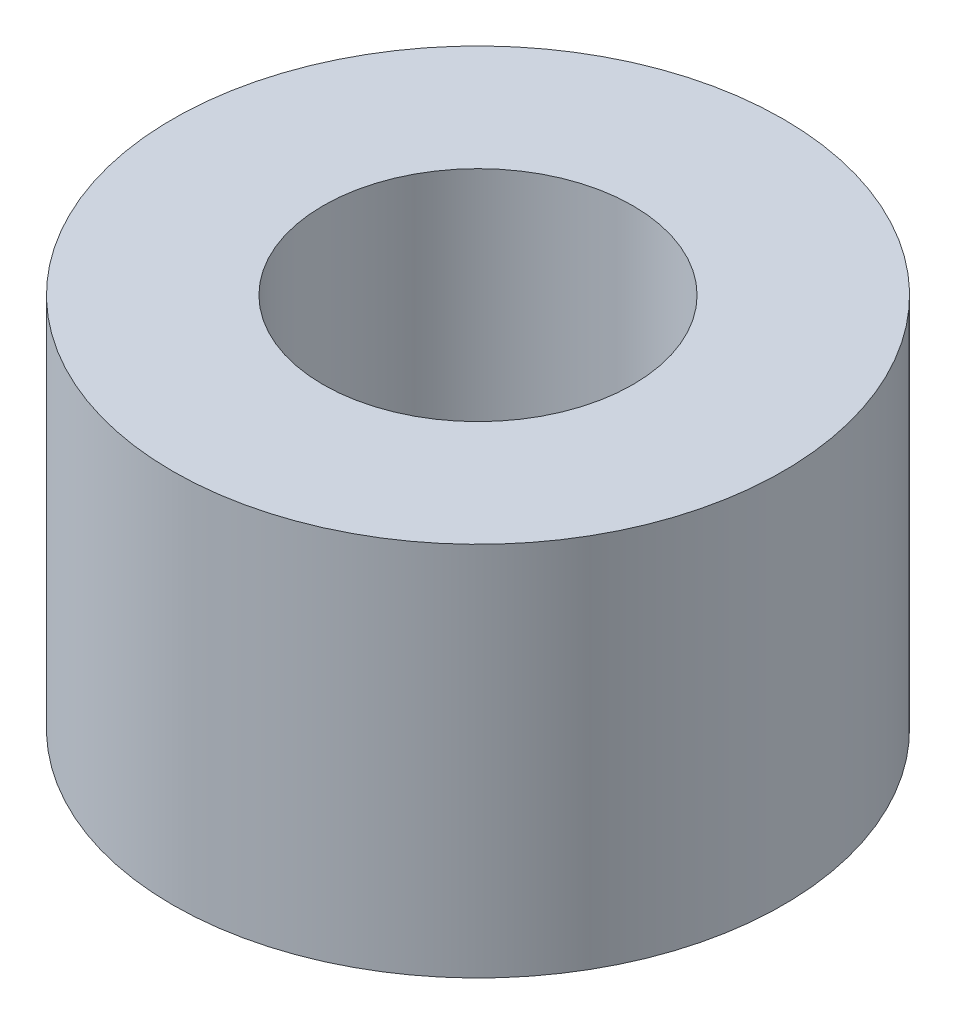
SolidWorks part; units mm, degrees
ref_plane "Front Plane" through (0, 0, 0) normal (0, 0, 1) x (1, 0, 0)
ref_plane "Top Plane" through (0, 0, 0) normal (0, 1, 0) x (1, 0, 0)
ref_plane "Right Plane" through (0, 0, 0) normal (1, 0, 0) x (0, 0, -1)
sketch "Sketch1" plane through (0, 0, 0) normal (0, 1, 0) x (1, 0, 0)
  circle A0 centre (0, 0) radius 1.65
  circle A1 centre (0, 0) radius 3.25
  dimension "D1" = 3.3
  dimension "D2" = 1.6
extrude "Boss-Extrude1" add sketch "Sketch1" along normal blind 4
